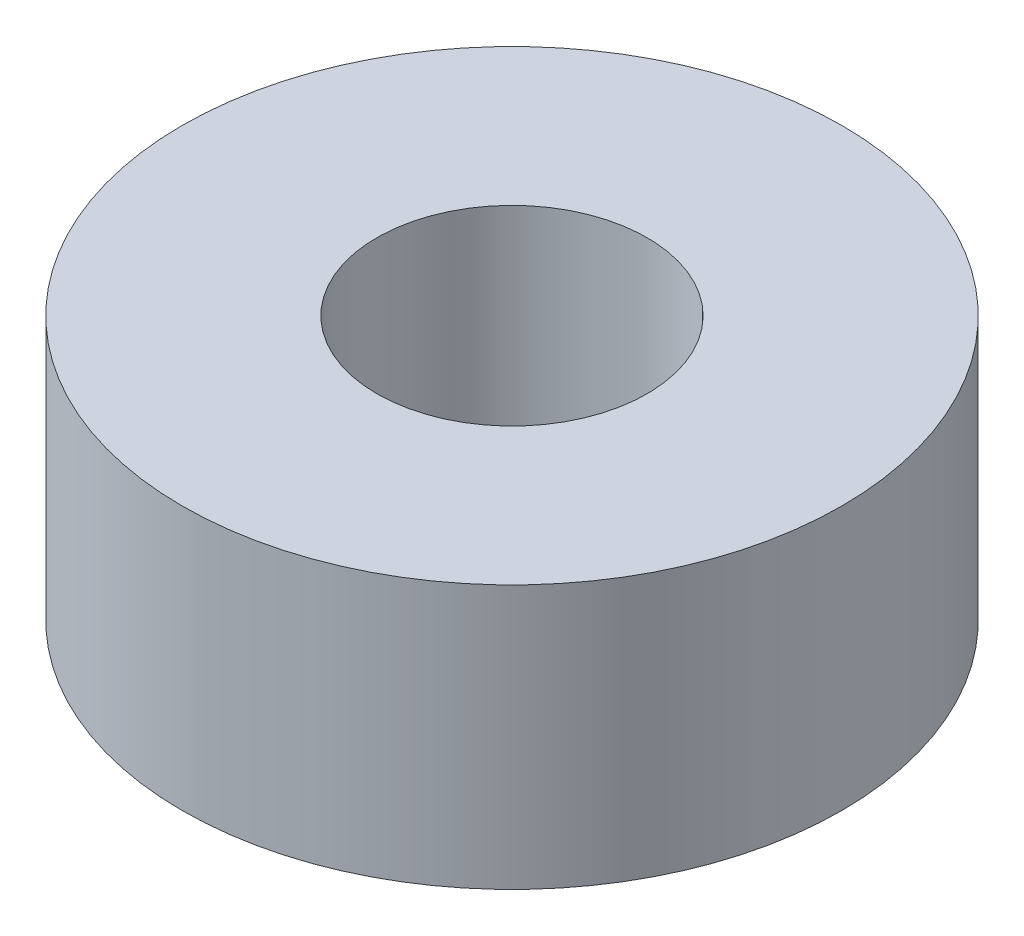
SolidWorks part; units mm, degrees
ref_plane "前视基准面" through (0, 0, 0) normal (0, 0, 1) x (1, 0, 0)
ref_plane "上视基准面" through (0, 0, 0) normal (0, 1, 0) x (1, 0, 0)
ref_plane "右视基准面" through (0, 0, 0) normal (1, 0, 0) x (0, 0, -1)
sketch "草图1" plane through (0, 0, 0) normal (0, 1, 0) x (1, 0, 0)
  circle A0 centre (0, 0) radius 5
  circle A1 centre (0, 0) radius 2.05
  dimension "D1" = 10
  dimension "D2" = 4.1
extrude "凸台-拉伸1" add sketch "草图1" along normal mid plane 4
